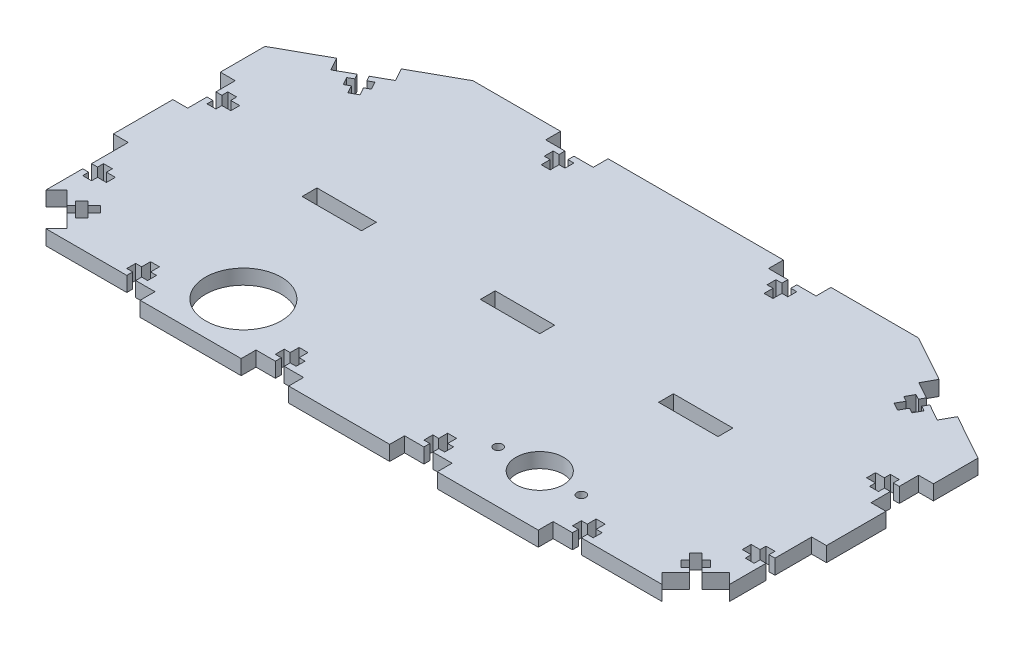
SolidWorks part; units mm, degrees
material "Trupan"
ref_plane "Alzado" through (0, 0, 0) normal (0, 0, 1) x (1, 0, 0)
ref_plane "Planta" through (0, 0, 0) normal (0, 1, 0) x (1, 0, 0)
ref_plane "Vista lateral" through (0, 0, 0) normal (1, 0, 0) x (0, 0, -1)
sketch "Croquis1" plane through (0, 0, 0) normal (0, 1, 0) x (1, 0, 0)
  line L1 (100, -60) -> (-100, -60)
  line L2 (100, -60) -> (100, 60)
  line L3 (100, 60) -> (-100, 60)
  line L4 (-100, -60) -> (-100, 60)
  line L5 (100, -60) -> (-100, 60) construction
  line L6 (100, 60) -> (-100, -60) construction
  point P0 (0, 0)
  dimension "D1" = 200
  dimension "D2" = 120
extrude "Saliente-Extruir1" add sketch "Croquis1" along normal blind 5
sketch "Croquis2" plane through (0, 5, 0) normal (0, 1, 0) x (1, 0, 0)
  line L1 (-100, -60) -> (-83, -60)
  line L2 (-100, -60) -> (-100, -55)
  line L3 (-100, -55) -> (-83, -55)
  line L4 (-83, -60) -> (-83, -55)
  line L5 (-83, -55) -> (-67, -55)
  line L6 (-83, -55) -> (-83, -60)
  line L7 (-83, -60) -> (-67, -60)
  line L8 (-67, -55) -> (-67, -60)
  line L9 (-67, -55) -> (-33, -55)
  line L10 (-67, -55) -> (-67, -60)
  line L11 (-67, -60) -> (-33, -60)
  line L12 (-33, -55) -> (-33, -60)
  line L13 (-33, -55) -> (-17, -55)
  line L14 (-33, -55) -> (-33, -60)
  line L15 (-33, -60) -> (-17, -60)
  line L16 (-17, -55) -> (-17, -60)
  line M10 (-100, -60) -> (100, -60)
  dimension "D1" = 17
  dimension "D2" = 5
  dimension "D3" = 16
  dimension "D4" = 34
  dimension "D5" = 16
extrude "Cortar-Extruir1" cut sketch "Croquis2" against normal through all contours L8 L5 L4 M10 | L16 L13 L12 M10
mirror "Simetría1" about plane through (0, 0, 0) normal (1, 0, 0) of "Cortar-Extruir1"
sketch "Croquis3" plane through (0, 5, 0) normal (0, 1, 0) x (1, 0, 0)
  line L0 (-83, -55) -> (-67, -55) construction
  line L1 (-73.5, -63) -> (-76.5, -63)
  line L2 (-73.5, -63) -> (-73.5, -47)
  line L3 (-73.5, -47) -> (-76.5, -47)
  line L4 (-76.5, -63) -> (-76.5, -47)
  line L5 (-73.5, -63) -> (-76.5, -47) construction
  line L6 (-73.5, -47) -> (-76.5, -63) construction
  line L7 (-33, -55) -> (-17, -55) construction
  line L8 (-78.5, -50) -> (-71.5, -50)
  line L9 (-78.5, -50) -> (-78.5, -53)
  line L10 (-78.5, -53) -> (-71.5, -53)
  line L11 (-71.5, -50) -> (-71.5, -53)
  line L12 (-23.5, -63) -> (-26.5, -63)
  line L13 (-23.5, -63) -> (-23.5, -47)
  line L14 (-23.5, -47) -> (-26.5, -47)
  line L15 (-26.5, -63) -> (-26.5, -47)
  line L16 (-23.5, -63) -> (-26.5, -47) construction
  line L17 (-23.5, -47) -> (-26.5, -63) construction
  line L19 (-28.5, -50) -> (-21.5, -50)
  line L20 (-28.5, -50) -> (-28.5, -53)
  line L21 (-28.5, -53) -> (-21.5, -53)
  line L22 (-21.5, -50) -> (-21.5, -53)
  point P0 (-75, -55)
  point P11 (-75, -53)
  point P12 (-25, -55)
  point P23 (-25, -53)
  line M24 (-83, -55) -> (-67, -55)
  line M28 (-33, -55) -> (-17, -55)
  dimension "D1" = 3
  dimension "D2" = 8
  dimension "D3" = 7
  dimension "D4" = 3
  dimension "D5" = 2
  dimension "D6" = 8
  dimension "D7" = 3
  dimension "D8" = 3
  dimension "D9" = 2
  dimension "D10" = 7
extrude "Cortar-Extruir2" cut sketch "Croquis3" against normal blind 10 contours L4 L1 L2 M24 | L9 L10 L4 L8 | L11 L8 L2 L10 | L10 L4 L2 M24 | L4 L8 L2 L3 | L4 L10 L2 L8 | L15 L19 L13 L14 | L22 L19 L13 L21 | L15 L21 L13 L19 | L20 L21 L15 L19 | L15 L12 L13 M28 | L21 L15 L13 M28
mirror "Simetría2" about plane through (0, 0, 0) normal (1, 0, 0) of "Cortar-Extruir2"
sketch "Croquis4" plane through (0, 5, 0) normal (0, 1, 0) x (1, 0, 0)
  line L0 (-100, 60) -> (-120, 80)
  line L1 (100, 60) -> (-100, 60) construction
  line L2 (-120, 80) -> (-120, -40)
  line L3 (-120, -40) -> (-100, -60)
  line L4 (-100, -60) -> (-83, -60) construction
  line L5 (-100, 60) -> (-100, -60) construction
  line L6 (-100, 60) -> (-100, -60)
  dimension "D1" = 135
  dimension "D2" = 135
  dimension "D3" = 20
extrude "Saliente-Extruir2" add sketch "Croquis4" against normal blind 5
sketch "Croquis5" plane through (0, 5, 0) normal (0, 1, 0) x (1, 0, 0)
  line L9 (-120, 80) -> (-120, 30)
  line L10 (-120, 80) -> (-120, -40) construction
  line L11 (-120, 30) -> (100, 30)
  line L12 (100, -60) -> (100, 60) construction
  line L13 (100, 30) -> (100, 60)
  line L14 (100, 60) -> (-100, 60)
  line L15 (-100, 60) -> (-120, 80)
  dimension "D1" = 30
mirror "Simetría4" about plane through (0, 0, 0) normal (1, 0, 0) of "Saliente-Extruir2"
sketch "Croquis6" plane through (0, 5, 0) normal (0, 1, 0) x (1, 0, 0)
  line L0 (-120, 80) -> (-120, 30)
  line L1 (-120, 80) -> (-120, -40) construction
  line L2 (-120, 30) -> (120, 30)
  line L3 (120, 80) -> (120, -40) construction
  line L4 (120, 30) -> (120, 80)
  line L5 (120, 80) -> (100, 60)
  line L6 (100, 60) -> (-100, 60)
  line L7 (-100, 60) -> (-120, 80)
  dimension "D1" = 30
extrude "Cortar-Extruir7" cut sketch "Croquis6" against normal through all
sketch "Croquis8" plane through (-80, 0, 80) normal (-0.7071, 0, 0.7071) x (0.7071, 0, 0.7071)
  line L0 (-56.5685, 5) -> (-28.2843, 5) construction
  line L1 (-50.4285, 5) -> (-34.4285, 5)
  line L2 (-50.4285, 5) -> (-50.4285, 0)
  line L3 (-50.4285, 0) -> (-34.4285, 0)
  line L4 (-34.4285, 5) -> (-34.4285, 0)
  line L5 (-56.5685, 0) -> (-28.2843, 0) construction
  line L6 (-56.5685, 0) -> (-56.5685, 5) construction
  point P8 (-42.4285, 0)
  dimension "D1" = 16
  dimension "D2" = 14.14
extrude "Cortar-Extruir8" cut sketch "Croquis8" against normal blind 5.93
sketch "Croquis9" plane through (0, 5, 0) normal (0, 1, 0) x (1, 0, 0)
  line L0 (-105.8084, -45.8053) -> (-100.1792, -40.1762) construction
  line L1 (-100.1515, -51.4622) -> (-111.4652, -40.1485) construction
  line L2 (-106.869, -44.7447) -> (-101.2122, -39.0878)
  line L3 (-100.1515, -51.4622) -> (-104.3447, -55.6553) construction
  line L4 (-104.7477, -46.866) -> (-99.0909, -41.2092)
  line L6 (-106.869, -44.7447) -> (-104.7477, -46.866)
  line L7 (-106.869, -41.9163) -> (-101.9193, -46.866)
  line L8 (-101.9193, -46.866) -> (-99.798, -44.7447)
  line L9 (-99.798, -44.7447) -> (-104.7477, -39.7949)
  line L10 (-104.7477, -39.7949) -> (-106.869, -41.9163)
  line L11 (-101.2122, -39.0878) -> (-99.0909, -41.2092)
  dimension "D1" = 1.5
  dimension "D2" = 1.5
  dimension "D3" = 8
  dimension "D5" = 3.5
  dimension "D6" = 3.5
  dimension "D7" = 3
  dimension "D8" = 2
extrude "Cortar-Extruir10" cut sketch "Croquis9" against normal blind 5
mirror "Simetría5" about plane through (0, 0, 0) normal (1, 0, 0) of "Cortar-Extruir8", "Cortar-Extruir10"
sketch "Croquis10" plane through (0, 5, 0) normal (0, 1, 0) x (1, 0, 0)
  line L0 (-120, 30) -> (-120, -40) construction
  line L1 (-120, 20) -> (-115, 20)
  line L2 (-120, 20) -> (-120, 4)
  line L3 (-120, 4) -> (-115, 4)
  line L4 (-115, 20) -> (-115, 4)
  line L6 (-120, -16) -> (-115, -16)
  line L7 (-120, -16) -> (-120, -46)
  line L8 (-120, -46) -> (-115, -46)
  line L9 (-115, -16) -> (-115, -46)
  line L10 (-120, 30) -> (120, 30) construction
  dimension "D1" = 16
  dimension "D2" = 30
  dimension "D3" = 5
  dimension "D4" = 5
  dimension "D5" = 10
  dimension "D6" = 20
extrude "Cortar-Extruir11" cut sketch "Croquis10" against normal through all
sketch "Croquis11" plane through (0, 5, 0) normal (0, 1, 0) x (1, 0, 0)
  line L0 (-115, 4) -> (-115, 20) construction
  line L1 (-115, 13.5) -> (-107, 13.5)
  line L2 (-115, 13.5) -> (-115, 10.5)
  line L3 (-115, 10.5) -> (-107, 10.5)
  line L4 (-107, 13.5) -> (-107, 10.5)
  line L5 (-115, -43.6833) -> (-115, -16) construction
  line L6 (-115, -28.3416) -> (-107, -28.3416)
  line L7 (-115, -28.3416) -> (-115, -31.3416)
  line L8 (-115, -31.3416) -> (-107, -31.3416)
  line L9 (-107, -28.3416) -> (-107, -31.3416)
  line L11 (-113, 15.5) -> (-110, 15.5)
  line L12 (-113, 15.5) -> (-113, 8.5)
  line L13 (-113, 8.5) -> (-110, 8.5)
  line L14 (-110, 15.5) -> (-110, 8.5)
  line L15 (-113, -26.3416) -> (-110, -26.3416)
  line L16 (-113, -26.3416) -> (-113, -33.3416)
  line L17 (-113, -33.3416) -> (-110, -33.3416)
  line L18 (-110, -26.3416) -> (-110, -33.3416)
  point P6 (-115, 12)
  point P7 (-115, 12)
  point P14 (-115, -29.8416)
  point P15 (-115, -29.8416)
  point P24 (-113, 12)
  point P25 (-113, -29.8416)
  dimension "D1" = 3
  dimension "D2" = 3
  dimension "D3" = 8
  dimension "D4" = 8
  dimension "D5" = 3
  dimension "D6" = 3
  dimension "D7" = 7
  dimension "D8" = 7
  dimension "D9" = 2
  dimension "D10" = 2
extrude "Cortar-Extruir12" cut sketch "Croquis11" against normal through all contours L1 L14 L3 L4 | L14 L1 L12 L3 | L14 L3 L12 L13 | L12 L1 L2 L3 | L14 L11 L12 L1 | L18 L6 L16 L8 | L18 L8 L16 L17 | L6 L18 L8 L9 | L18 L15 L16 L6 | L16 L6 L7 L8
mirror "Simetría6" about plane through (0, 0, 0) normal (1, 0, 0) of "Cortar-Extruir12", "Cortar-Extruir11"
sketch "Croquis12" plane through (0, 5, 0) normal (0, 1, 0) x (1, 0, 0)
  line L0 (-83, -55) -> (-83, -60)
  line L1 (-83, -60) -> (-100, -60)
  line L2 (-100, -60) -> (-104.3447, -55.6553)
  line L3 (-83, -55) -> (-103.6893, -55)
  line L4 (-100.1515, -51.4622) -> (-104.3447, -55.6553) construction
  line L5 (-103.6893, -55) -> (-104.3447, -55.6553)
extrude "Cortar-Extruir13" cut sketch "Croquis12" against normal through all
mirror "Simetría7" about plane through (0, 0, 0) normal (1, 0, 0) of "Cortar-Extruir13"
sketch "Croquis15" plane through (0, 5, 0) normal (0, 1, 0) x (1, 0, 0)
  line L0 (-67, -60) -> (-33, -60) construction
  line L1 (33, -60) -> (67, -60) construction
  line L2 (-33, -55) -> (-26.5, -55) construction
  circle A0 centre (-50, -42.25) radius 12.75
  circle A1 centre (50, -42.5) radius 8
  point P6 (-50, -60)
  point P9 (50, -60)
  dimension "D1" = 25.5
  dimension "D2" = 16
  dimension "D3" = 17.5
extrude "Cortar-Extruir15" cut sketch "Croquis15" against normal through all
sketch "Croquis17" plane through (0, 5, 0) normal (0, 1, 0) x (1, 0, 0)
  line L1 (-120, 60) -> (120, 60)
  line L2 (-120, 60) -> (-120, 30)
  line L3 (-120, 30) -> (120, 30)
  line L4 (120, 60) -> (120, 30)
  dimension "D1" = 30
extrude "Saliente-Extruir3" add sketch "Croquis17" against normal blind 5
sketch "Croquis18" plane through (0, 5, 0) normal (0, 1, 0) x (1, 0, 0)
  line L0 (-75, 60) -> (-120, 35)
  line L1 (120, 60) -> (-120, 60) construction
  line L2 (-120, 60) -> (-120, 20) construction
  line L3 (-120, 35) -> (-120, 60)
  line L4 (-120, 60) -> (-75, 60)
  dimension "D1" = 25
  dimension "D2" = 45
extrude "Cortar-Extruir18" cut sketch "Croquis18" against normal through all
mirror "Simetría8" about plane through (0, 0, 0) normal (1, 0, 0) of "Cortar-Extruir18"
sketch "Croquis19" plane through (0, 5, 0) normal (0, 1, 0) x (1, 0, 0)
  line L0 (-78.0743, 12.5337) -> (-116.9257, 82.4663) construction
  line L2 (-120, 35) -> (-75, 60) construction
  line L3 (-102.065, 39.2441) -> (-96.383, 42.4007)
  line L4 (-104.4933, 43.6149) -> (-102.065, 39.2441)
  line L5 (-96.383, 42.4007) -> (-95.4117, 40.6524)
  line L6 (-95.4117, 40.6524) -> (-97.16, 39.6811)
  line L7 (-97.16, 39.6811) -> (-95.7031, 37.0587)
  line L8 (-95.7031, 37.0587) -> (-93.9548, 38.03)
  line L9 (-93.9548, 38.03) -> (-92.4979, 35.4075)
  line L10 (-92.4979, 35.4075) -> (-89.8754, 36.8644)
  line L11 (-104.4933, 43.6149) -> (-90.5067, 51.3851)
  line L12 (-89.584, 40.4582) -> (-91.3323, 39.4869)
  line L13 (-91.3323, 39.4869) -> (-89.8754, 36.8644)
  line L14 (-91.0409, 43.0806) -> (-89.584, 40.4582)
  line L15 (-92.7893, 42.1094) -> (-91.0409, 43.0806)
  line L16 (-93.7605, 43.8577) -> (-92.7893, 42.1094)
  line L17 (-88.0785, 47.0144) -> (-93.7605, 43.8577)
  line L18 (-90.5067, 51.3851) -> (-88.0785, 47.0144)
  point P3 (-97.5, 47.5)
  point P18 (-91.1866, 36.136)
  point P23 (-97.5, 47.5)
  dimension "D1" = 80
  dimension "D2" = 6.5
  dimension "D3" = 5
  dimension "D4" = 2
  dimension "D5" = 2
  dimension "D6" = 3
  dimension "D7" = 3
  dimension "D8" = 8
  dimension "D9" = 3
extrude "Cortar-Extruir19" cut sketch "Croquis19" against normal through all
mirror "Simetría9" about plane through (0, 0, 0) normal (1, 0, 0) of "Cortar-Extruir19"
sketch "Croquis20" plane through (0, 5, 0) normal (0, 1, 0) x (1, 0, 0)
  line L0 (-37.5, 60) -> (-37.5, 82.6247) construction
  line L2 (75, 60) -> (-75, 60) construction
  line L4 (-29.5, 65) -> (-45.5, 65)
  line L5 (-29.5, 65) -> (-29.5, 55)
  line L6 (-29.5, 55) -> (-45.5, 55)
  line L7 (-45.5, 65) -> (-45.5, 55)
  line L8 (-29.5, 65) -> (-45.5, 55) construction
  line L9 (-29.5, 55) -> (-45.5, 65) construction
  line L10 (-36, 63) -> (-39, 63)
  line L11 (-36, 63) -> (-36, 47)
  line L12 (-36, 47) -> (-39, 47)
  line L13 (-39, 63) -> (-39, 47)
  line L14 (-36, 63) -> (-39, 47) construction
  line L15 (-36, 47) -> (-39, 63) construction
  line L16 (-34, 50) -> (-41, 50)
  line L17 (-34, 50) -> (-34, 53)
  line L18 (-34, 53) -> (-41, 53)
  line L19 (-41, 50) -> (-41, 53)
  line L20 (-34, 50) -> (-41, 53) construction
  line L21 (-34, 53) -> (-41, 50) construction
  point P11 (-37.5, 55)
  point P16 (-37.5, 51.5)
  dimension "D1" = 37.5
  dimension "D2" = 16
  dimension "D3" = 5
  dimension "D4" = 8
  dimension "D5" = 3
  dimension "D6" = 2
  dimension "D7" = 3
  dimension "D8" = 7
extrude "Cortar-Extruir20" cut sketch "Croquis20" against normal through all contours L13 L10 L11 L6 L5 L4 L7 | L17 L18 L11 L16 | L19 L16 L13 L18
mirror "Simetría10" about plane through (0, 0, 0) normal (1, 0, 0) of "Cortar-Extruir20"
sketch "Croquis24" plane through (0, 5, 0) normal (0, 1, 0) x (1, 0, 0)
  line L1 (-50, -2.5) -> (-70, -2.5)
  line L2 (-50, -2.5) -> (-50, 2.5)
  line L3 (-50, 2.5) -> (-70, 2.5)
  line L4 (-70, -2.5) -> (-70, 2.5)
  line L5 (-50, -2.5) -> (-70, 2.5) construction
  line L6 (-50, 2.5) -> (-70, -2.5) construction
  point P0 (-60, 0)
  dimension "D1" = 60
  dimension "D2" = 5
  dimension "D3" = 20
  dimension "D4" = 0
extrude "Cortar-Extruir25" cut sketch "Croquis24" against normal through all
mirror "Simetría11" about plane through (0, 0, 0) normal (1, 0, 0) of "Cortar-Extruir25"
sketch "Croquis25" plane through (0, 5, 0) normal (0, 1, 0) x (1, 0, 0)
  line L1 (10, -2.5) -> (-10, -2.5)
  line L2 (10, -2.5) -> (10, 2.5)
  line L3 (10, 2.5) -> (-10, 2.5)
  line L4 (-10, -2.5) -> (-10, 2.5)
  line L5 (10, -2.5) -> (-10, 2.5) construction
  line L6 (10, 2.5) -> (-10, -2.5) construction
  point P0 (0, 0)
  dimension "D1" = 5
  dimension "D2" = 20
extrude "Cortar-Extruir26" cut sketch "Croquis25" against normal through all
sketch "Croquis26" plane through (0, 5, 0) normal (0, 1, 0) x (1, 0, 0)
  line L1 (33, -55) -> (26.5, -55) construction
  line L2 (73.5, -55) -> (67, -55) construction
  circle A0 centre (36, -42.5) radius 1.5
  circle A1 centre (64, -42.5) radius 1.5
  circle A2 centre (50, -42.5) radius 8 construction
  dimension "D2" = 14
  dimension "D3" = 3
  dimension "D4" = 3
  dimension "D5" = 12.5
  dimension "D1" = 14
  dimension "D6" = 12.5
extrude "Cortar-Extruir28" cut sketch "Croquis26" against normal through all
